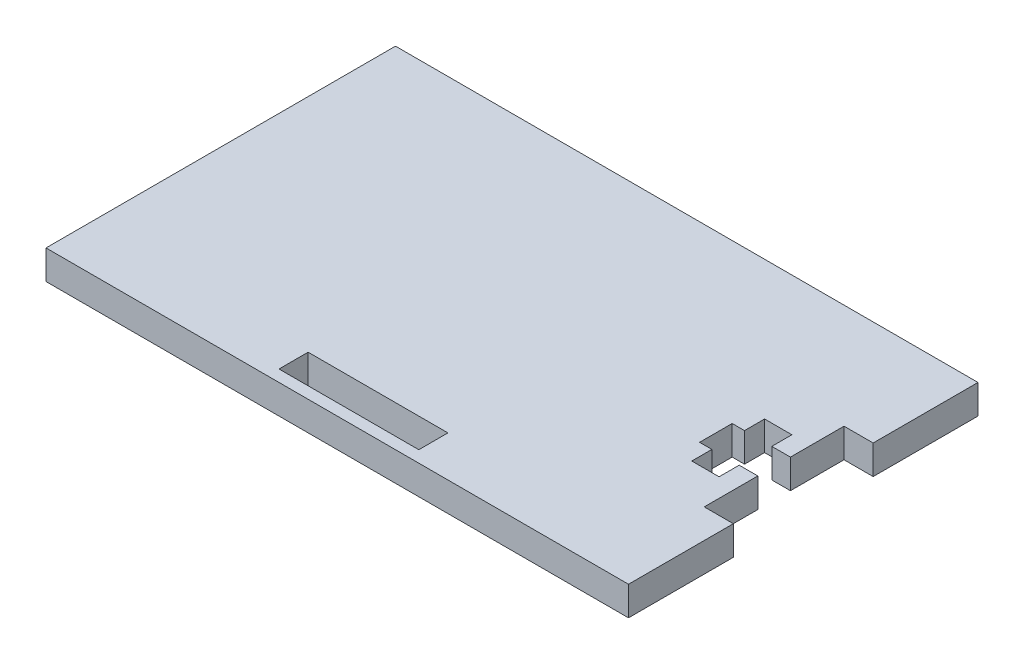
SolidWorks part; units mm, degrees
ref_plane "Front Plane" through (0, 0, 0) normal (0, 0, 1) x (1, 0, 0)
ref_plane "Top Plane" through (0, 0, 0) normal (0, 1, 0) x (1, 0, 0)
ref_plane "Right Plane" through (0, 0, 0) normal (1, 0, 0) x (0, 0, -1)
sketch "Sketch1" plane through (0, 0, 0) normal (0, 1, 0) x (1, 0, 0)
  line L0 (31.75, 38.1) -> (31.75, -50.4791) construction
  line L1 (0, 0) -> (63.5, 0)
  line L2 (0, 0) -> (0, 38.1)
  line L3 (0, 38.1) -> (63.5, 38.1)
  line L4 (63.5, 0) -> (63.5, 11.43)
  line L5 (24.13, 4.445) -> (39.37, 4.445)
  line L6 (24.13, 4.445) -> (24.13, 1.27)
  line L7 (24.13, 1.27) -> (39.37, 1.27)
  line L8 (39.37, 4.445) -> (39.37, 1.27)
  line L9 (63.5, 19.05) -> (24.7475, 19.05) construction
  line L10 (63.5, 26.67) -> (60.325, 26.67)
  line L11 (60.325, 26.67) -> (60.325, 20.828)
  line L12 (60.325, 11.43) -> (63.5, 11.43)
  line L13 (58.293, 20.828) -> (60.325, 20.828)
  line L14 (55.3164, 23.0187) -> (58.293, 23.0188)
  line L15 (55.3164, 23.0187) -> (55.3164, 20.828)
  line L16 (55.3164, 15.0812) -> (58.293, 15.0812)
  line L17 (58.293, 23.0188) -> (58.293, 20.828)
  line L18 (53.975, 20.828) -> (55.3164, 20.828)
  line L19 (53.975, 20.828) -> (53.975, 17.272)
  line L20 (53.975, 17.272) -> (55.3164, 17.272)
  line L21 (60.325, 17.272) -> (60.325, 11.43)
  line L22 (55.3164, 17.272) -> (55.3164, 15.0812)
  line L23 (58.293, 17.272) -> (60.325, 17.272)
  line L24 (58.293, 17.272) -> (58.293, 15.0812)
  line L25 (63.5, 26.67) -> (63.5, 38.1)
  dimension "D1" = 38.1
  dimension "D2" = 63.5
  dimension "D3" = 15.24
  dimension "D4" = 7.62
  dimension "D5" = 1.27
  dimension "D6" = 3.175
  dimension "D7" = 7.62
  dimension "D8" = 7.62
  dimension "D9" = 3.9688
  dimension "D10" = 7.9375
  dimension "D11" = 2.9766
  dimension "D12" = 2.032
  dimension "D13" = 3.175
  dimension "D14" = 1.778
  dimension "D16" = 6.35
extrude "Boss-Extrude1" add sketch "Sketch1" along normal blind 3.175
